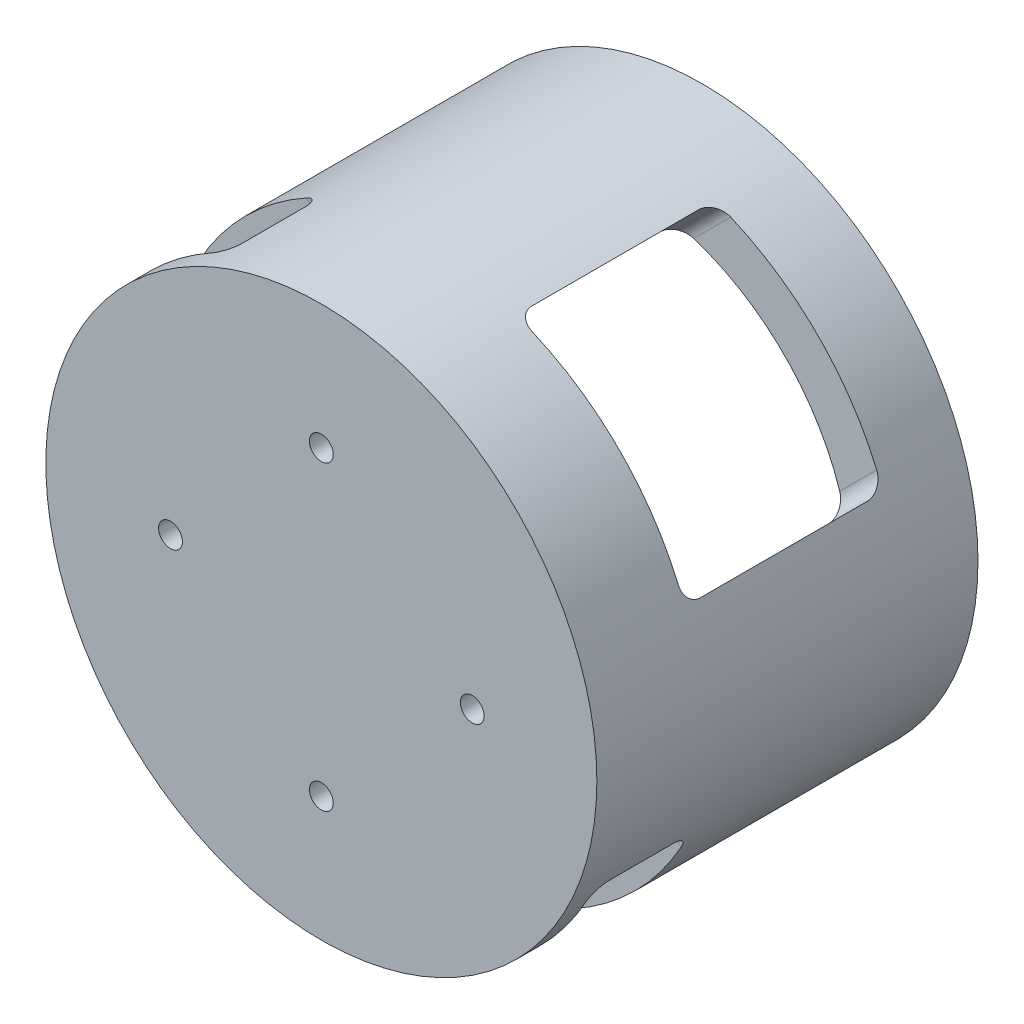
SolidWorks part; units mm, degrees
ref_plane "前视基准面" through (0, 0, 0) normal (0, 0, 1) x (1, 0, 0)
ref_plane "上视基准面" through (0, 0, 0) normal (0, 1, 0) x (1, 0, 0)
ref_plane "右视基准面" through (0, 0, 0) normal (1, 0, 0) x (0, 0, -1)
other "Configuration Table"
sketch "草图1" plane through (0, 0, 0) normal (0, 0, 1) x (1, 0, 0)
  line L0 (0, 19) -> (0, 0) construction
  circle A0 centre (0, 19) radius 1.5
  circle A1 centre (0, 0) radius 28.7
  circle A2 centre (19, 0) radius 1.5
  circle A3 centre (0, -19) radius 1.5
  circle A4 centre (-19, 0) radius 1.5
  point P14 (0, 0)
  dimension "D1" = 3
  dimension "D3" = 57.4
  dimension "D2" = 19
  dimension "D4" = 4
extrude "凸台-拉伸1" add sketch "草图1" along normal blind 3
sketch "草图2" plane through (0, 0, 3) normal (0, 0, 1) x (1, 0, 0)
  circle A0 centre (0, 0) radius 34.7
  circle A1 centre (0, 0) radius 28.7
  circle A2 centre (0, 0) radius 28.7
  dimension "D1" = 0
  dimension "D2" = 6
extrude "凸台-拉伸2" add sketch "草图2" against normal blind 48
ref_plane "基准面1" through (-24.5366, 24.5366, 0) normal (-0.7071, 0.7071, 0) x (0, 0, 1)
sketch "草图3" plane through (-24.5366, 24.5366, 0) normal (-0.7071, 0.7071, 0) x (0, 0, 1)
  line L0 (0, 28.7) -> (0, -28.7) construction
  line L1 (0, 28.7) -> (0, -28.7)
  line L2 (-12, -11.5) -> (0, -11.5)
  line L3 (-12, -11.5) -> (-12, 11.5)
  line L4 (0, -11.5) -> (0, 11.5)
  line L5 (-12, 11.5) -> (0, 11.5)
  line L6 (-12, -11.5) -> (0, 11.5) construction
  line L7 (0, -11.5) -> (-12, 11.5) construction
  point P3 (-6, 0)
  point P4 (0, 0)
  dimension "D1" = 12
  dimension "D2" = 23
extrude "切除-拉伸1" cut sketch "草图3" against normal through all contours L5 L3 L2 L1
fillet "圆角1" radius 2 8 edges at (-12.74, 29.0035, 0) (29.0035, -12.74, 0) (-29.0035, 12.74, 0) (12.74, -29.0035, 0) (12.74, -29.0035, -12) (-29.0035, 12.74, -12) (-12.74, 29.0035, -12) (29.0035, -12.74, -12)
ref_plane "基准面2" through (24.5366, 24.5366, 0) normal (0.7071, 0.7071, 0) x (0.7071, -0.7071, 0)
sketch "草图4" plane through (24.5366, 24.5366, 0) normal (0.7071, 0.7071, 0) x (0.7071, -0.7071, 0)
  line L0 (27.0821, 0) -> (-27.0821, 0) construction
  line L1 (27.0821, 0) -> (-27.0821, 0)
  line L2 (34.7, 45) -> (-34.7, 45) construction
  line L3 (-15, 35) -> (15, 35)
  line L4 (-15, 35) -> (-15, 10)
  line L5 (-15, 10) -> (15, 10)
  line L6 (15, 35) -> (15, 10)
  line L7 (-15, 35) -> (15, 10) construction
  line L8 (-15, 10) -> (15, 35) construction
  point P2 (0, 22.5)
  point P8 (0, 0)
  dimension "D1" = 10
  dimension "D2" = 10
  dimension "D3" = 30
extrude "切除-拉伸2" cut sketch "草图4" against normal through all contours L6 L3 L4 L5
fillet "圆角2" radius 2 8 edges at (-9.107, -30.3202, -35) (30.3202, 9.107, -35) (-30.3202, -9.107, -35) (9.107, 30.3202, -35) (-30.3202, -9.107, -10) (9.107, 30.3202, -10) (-9.107, -30.3202, -10) (30.3202, 9.107, -10)
